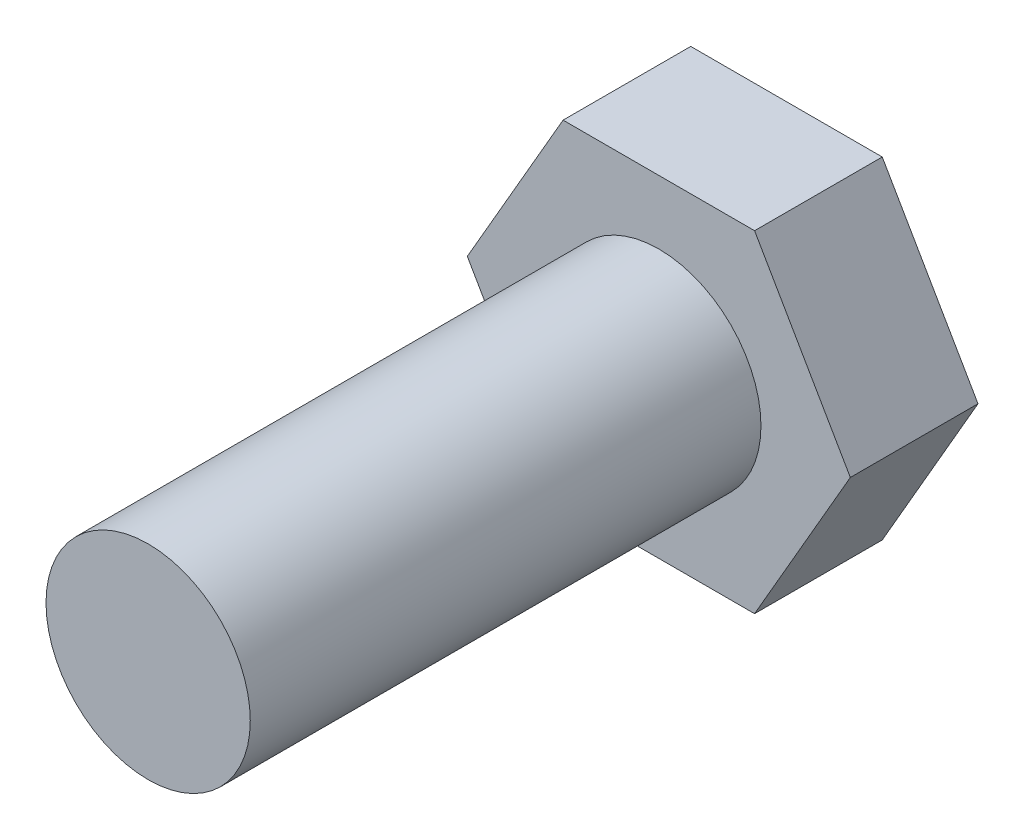
SolidWorks part; units mm, degrees
ref_plane "前视基准面" through (0, 0, 0) normal (0, 0, 1) x (1, 0, 0)
ref_plane "上视基准面" through (0, 0, 0) normal (0, 1, 0) x (1, 0, 0)
ref_plane "右视基准面" through (0, 0, 0) normal (1, 0, 0) x (0, 0, -1)
other "Configuration Table"
sketch "草图1" plane through (0, 0, 0) normal (0, 0, 1) x (1, 0, 0)
  line L1 (15, 0) -> (7.5, 12.9904)
  line L2 (7.5, 12.9904) -> (-7.5, 12.9904)
  line L3 (-7.5, 12.9904) -> (-15, 0)
  line L4 (-15, 0) -> (-7.5, -12.9904)
  line L5 (-7.5, -12.9904) -> (7.5, -12.9904)
  line L6 (7.5, -12.9904) -> (15, 0)
  circle A0 centre (0, 0) radius 12.9904 construction
extrude "凸台-拉伸1" add sketch "草图1" along normal blind 10
sketch "草图2" plane through (0, 0, 0) normal (0, 0, 1) x (1, 0, 0)
  circle A0 centre (0, 0) radius 8
extrude "凸台-拉伸2" add sketch "草图2" along normal blind 50
sketch "草图3" plane through (0, 0, 0) normal (0, 0, 1) x (1, 0, 0)
  circle A0 centre (0, 0) radius 4
extrude "切除-拉伸2" cut sketch "草图3" along normal blind 15
